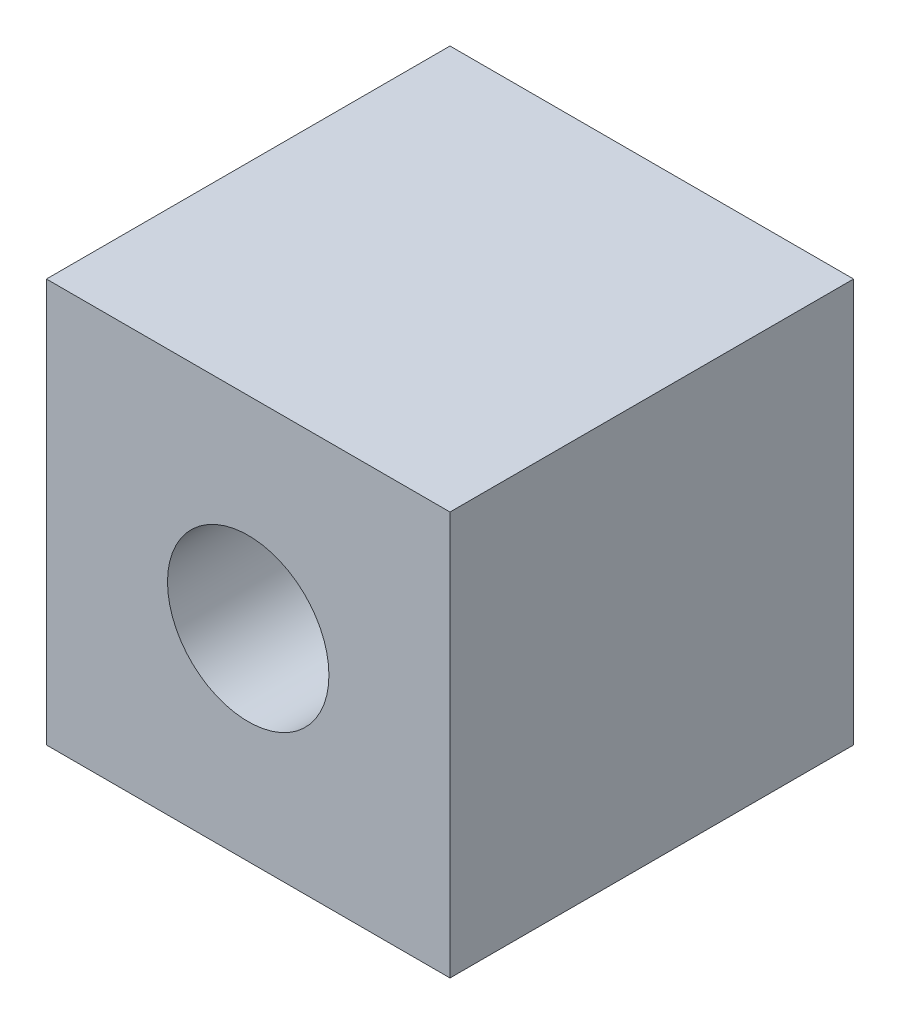
SolidWorks part; units mm, degrees
ref_plane "Спереди" through (0, 0, 0) normal (0, 0, 1) x (1, 0, 0)
ref_plane "Сверху" through (0, 0, 0) normal (0, 1, 0) x (1, 0, 0)
ref_plane "Справа" through (0, 0, 0) normal (1, 0, 0) x (0, 0, -1)
sketch "Эскиз1" plane through (0, 0, 0) normal (0, 0, 1) x (1, 0, 0)
  line L1 (-25, -25) -> (25, -25)
  line L2 (-25, -25) -> (-25, 25)
  line L3 (-25, 25) -> (25, 25)
  line L4 (25, -25) -> (25, 25)
  line L5 (-25, -25) -> (25, 25) construction
  line L6 (-25, 25) -> (25, -25) construction
  point P0 (0, 0)
  dimension "D1" = 50
extrude "Бобышка-Вытянуть1" add sketch "Эскиз1" along normal blind 50
sketch "Эскиз2" plane through (0, 0, 50) normal (0, 0, 1) x (1, 0, 0)
  circle A0 centre (0, 0) radius 10
  dimension "D1" = 20
extrude "Вырез-Вытянуть1" cut sketch "Эскиз2" against normal through all
